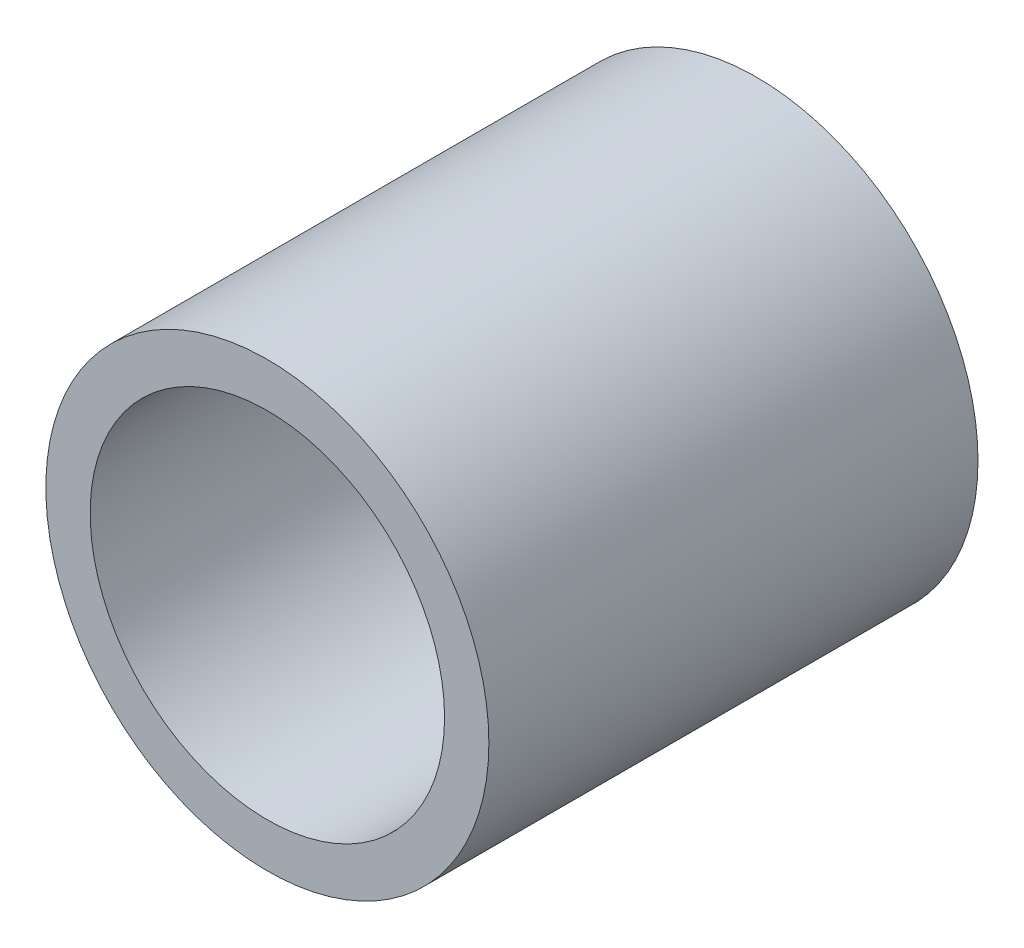
SolidWorks part; units mm, degrees
ref_plane "Front Plane" through (0, 0, 0) normal (0, 0, 1) x (1, 0, 0)
ref_plane "Top Plane" through (0, 0, 0) normal (0, 1, 0) x (1, 0, 0)
ref_plane "Right Plane" through (0, 0, 0) normal (1, 0, 0) x (0, 0, -1)
sketch "Sketch1" plane through (0, 0, 0) normal (0, 0, 1) x (1, 0, 0)
  circle A0 centre (0, 0) radius 0.5
  circle A1 centre (0, 0) radius 0.625
  dimension "D1" = 1
  dimension "D2" = 1.25
extrude "Boss-Extrude1" add sketch "Sketch1" along normal blind 1.38
